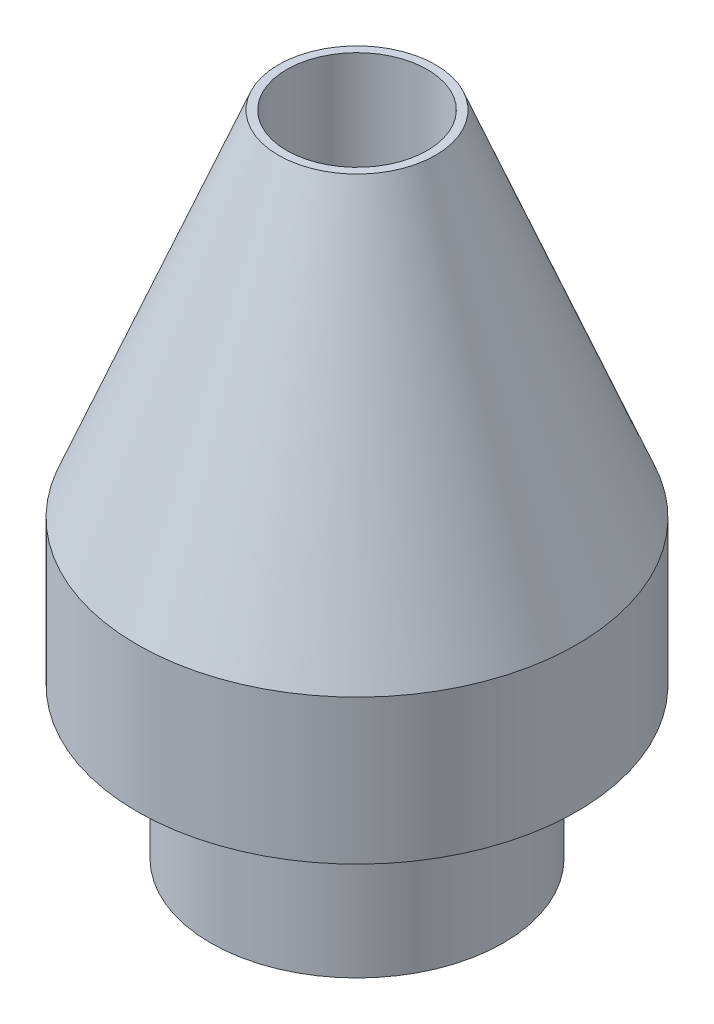
SolidWorks part; units mm, degrees
ref_plane "Front Plane" through (0, 0, 0) normal (0, 0, 1) x (1, 0, 0)
ref_plane "Top Plane" through (0, 0, 0) normal (0, 1, 0) x (1, 0, 0)
ref_plane "Right Plane" through (0, 0, 0) normal (1, 0, 0) x (0, 0, -1)
sketch "Sketch1" plane through (0, 0, 0) normal (0, 1, 0) x (1, 0, 0)
  circle A0 centre (0, 0) radius 6.2992
  dimension "D1" = 12.5984
extrude "Boss-Extrude1" add sketch "Sketch1" along normal blind 6.477
sketch "Sketch2" plane through (0, 6.477, 0) normal (0, 1, 0) x (1, 0, 0)
  circle A0 centre (0, 0) radius 9.4615
  dimension "D1" = 18.923
extrude "Boss-Extrude2" add sketch "Sketch2" along normal blind 6.223
sketch "Sketch5" plane through (0, 12.7, 0) normal (0, 1, 0) x (1, 0, 0)
  circle A0 centre (0, 0) radius 9.4615 construction
  circle A1 centre (0, 0) radius 9.4615
ref_plane "Plane1" through (0, 27.8892, 0) normal (0, 1, 0) x (1, 0, 0)
sketch "Sketch6" plane through (0, 27.8892, 0) normal (0, 1, 0) x (1, 0, 0)
  circle A0 centre (0, 0) radius 3.3782
  dimension "D1" = 6.7564
loft "Loft2" add profiles "Sketch5", "Sketch6"
sketch "Sketch7" plane through (0, 27.8892, 0) normal (0, 1, 0) x (1, 0, 0)
  circle A0 centre (0, 0) radius 3.0226
  dimension "D1" = 6.0452
extrude "Cut-Extrude1" cut sketch "Sketch7" against normal through all
